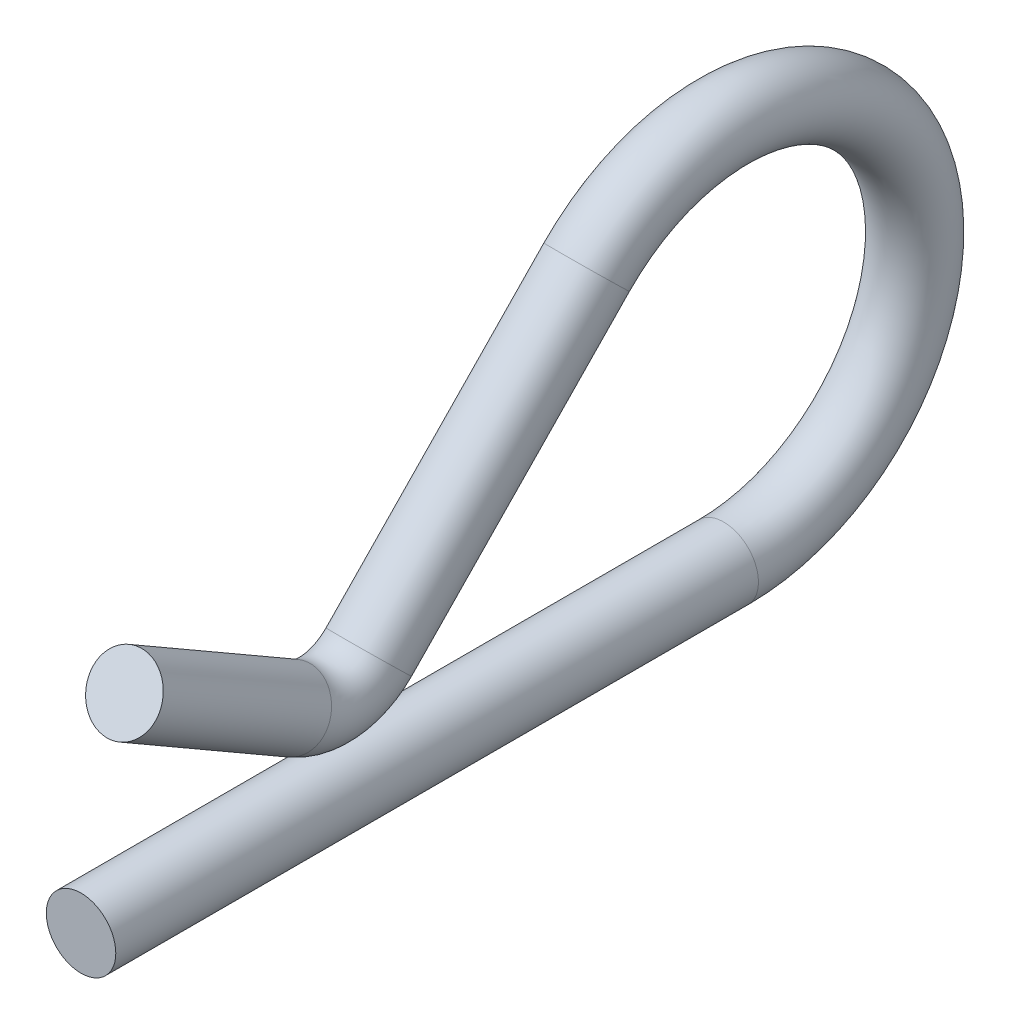
SolidWorks part; units mm, degrees
other "Imported1" parameters "D2"=5.0181, "D6"=6.8835, "D7"=12, "D8"=3.8089, "D10"=2.9762, "D1"=2.286, "D11"=3.7756, "D12"=2.286, "D13"=11.4644, "Eye Diameter"=14.2748, "D3"=15.2738, "D4"=16.0154, "D5"=5.7496, "D9"=5.935, "L"=29.9693, "Length"=130.175, "Wire Diameter"=3.175, "Gap"=1.4542, "Length to Bend"=28.575, "Length to Bent End"=38.4861, "Height to Bent End"=11.4656
ref_plane "Front" through (0, 0, 0) normal (0, 0, 1) x (1, 0, 0)
ref_plane "Top" through (0, 0, 0) normal (0, 1, 0) x (1, 0, 0)
ref_plane "Right" through (0, 0, 0) normal (1, 0, 0) x (0, 0, -1)
sketch "Sketch1" plane through (0, 0, 0) normal (1, 0, 0) x (0, 0, -1)
  line L1 (-29.3624, 1.5875) -> (-28.8544, 1.5875) construction
  line L2 (10.3124, -11.1735) -> (10.3124, 8.7249) construction
  line L3 (10.3124, 8.7249) -> (8.7249, 8.7249) construction
  line L4 (-29.3624, 0) -> (-29.3624, 1.5875) construction
  line L5 (0, 0) -> (-29.3624, 0) construction
  line L7 (-19.6895, 4.0652) -> (-27.3802, 8.5031) construction
  line L8 (-29.3624, 0) -> (-29.3624, -1.5875) construction
  line L9 (-28.1737, 7.1281) -> (-26.5868, 9.8781) construction
  line L10 (-29.3624, 1.5875) -> (-29.3624, -1.5875) construction
  line L13 (-6.26, 14.8024) -> (-16.2142, 4.5493) construction
  circle A0 centre (0, 8.7249) radius 7.1374 construction
  arc A6 (-16.2142, 4.5493) -> (-19.6895, 4.0652) centre (-18.2626, 6.538) cw construction
  arc A9 (0, 0) -> (-6.26, 14.8024) centre (0, 8.7249) ccw construction
  point P2 (0, 0)
  point P10 (-18.2626, 3.683)
  point P16 (-27.3802, 8.5031)
  point P20 (-29.3624, 0)
  dimension "D6" = 2.855
  dimension "D11" = 1.5875
  dimension "D3" = 1.5875
  dimension "Gap" = 0.508
  dimension "Length" = 39.6748
  dimension "D5" = 3.683
ref_plane "Plane1" through (0, 0, 29.3624) normal (0, 0, 1) x (1, 0, 0)
sketch "Sketch2" plane through (0, 0, 29.3624) normal (0, 0, 1) x (1, 0, 0)
  circle A0 centre (0, 0) radius 1.5875
sketch "Sketch3" plane through (0, 0, 0) normal (1, 0, 0) x (0, 0, -1)
  line L3 (-6.26, 14.8024) -> (-16.2142, 4.5493) construction
  line L6 (-6.26, 14.8024) -> (-16.2142, 4.5493)
  line L7 (-19.6895, 4.0652) -> (-27.3802, 8.5031) construction
  line L8 (0, 0) -> (-29.3624, 0) construction
  line L9 (-19.6895, 4.0652) -> (-27.3802, 8.5031)
  line L10 (0, 0) -> (-29.3624, 0)
  arc A4 (0, 0) -> (-6.26, 14.8024) centre (0, 8.7249) ccw construction
  arc A5 (-19.6895, 4.0652) -> (-16.2142, 4.5493) centre (-18.2626, 6.538) ccw construction
  arc A6 (0, 0) -> (-6.26, 14.8024) centre (0, 8.7249) ccw
  arc A7 (-19.6895, 4.0652) -> (-16.2142, 4.5493) centre (-18.2626, 6.538) ccw
sweep "Sweep1" add profiles "Sketch2" path "Sketch3"
equation "\"D11@Sketch1\" = \"Wire Diameter@Sketch1\" / 2"
equation "\"D3@Sketch1\" = \"D11@Sketch1\""
equation "\"D5@Sketch1\" = \"Gap@Sketch1\" + \"Wire Diameter@Sketch1\""
equation "\"D6@Sketch1\" = \"Eye Diameter@Sketch1\" * .2"
